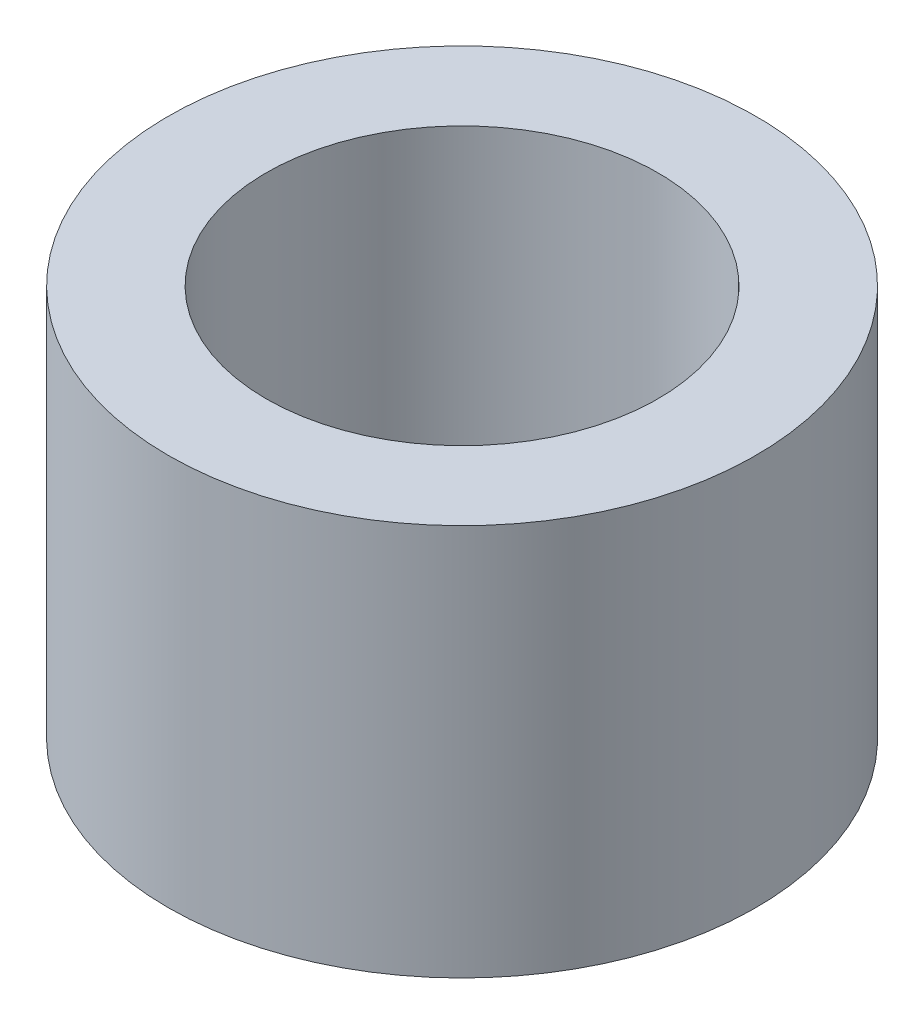
SolidWorks part; units mm, degrees
material "policarbonato"
ref_plane "Alzado" through (0, 0, 0) normal (0, 0, 1) x (1, 0, 0)
ref_plane "Planta" through (0, 0, 0) normal (0, 1, 0) x (1, 0, 0)
ref_plane "Vista lateral" through (0, 0, 0) normal (1, 0, 0) x (0, 0, -1)
sketch "Sketch1" plane through (0, 0, 0) normal (0, 1, 0) x (1, 0, 0)
  circle A0 centre (0, 0) radius 1.6
  circle A1 centre (0, 0) radius 2.4
  dimension "D1" = 3.2
  dimension "D2" = 4.8
extrude "Boss-Extrude1" add sketch "Sketch1" along normal blind 3.2
